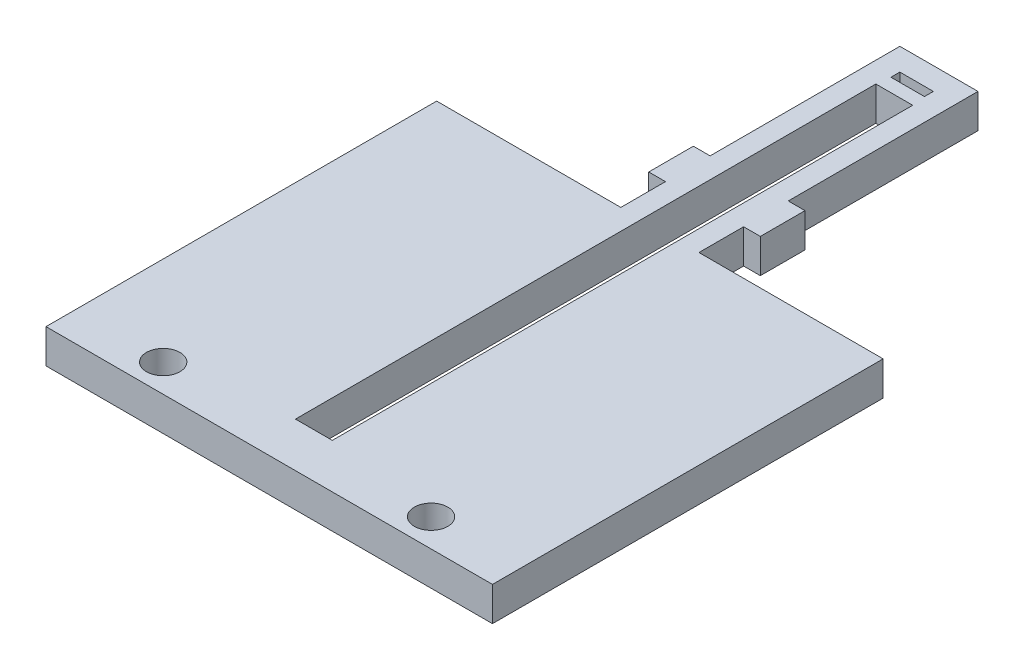
SolidWorks part; units mm, degrees
ref_plane "Front Plane" through (0, 0, 0) normal (0, 0, 1) x (1, 0, 0)
ref_plane "Top Plane" through (0, 0, 0) normal (0, 1, 0) x (1, 0, 0)
ref_plane "Right Plane" through (0, 0, 0) normal (1, 0, 0) x (0, 0, -1)
sketch "Sketch1" plane through (0, 0, 0) normal (0, 1, 0) x (1, 0, 0)
  line L1 (0, 0) -> (40, 0)
  line L2 (0, 0) -> (0, 60)
  line L3 (0, 60) -> (40, 60)
  line L4 (40, 0) -> (40, 60)
  dimension "D1" = 40
  dimension "D2" = 60
extrude "Boss-Extrude1" add sketch "Sketch1" along normal blind 3.05
sketch "Sketch4" plane through (0, 3.05, 0) normal (0, 1, 0) x (1, 0, 0)
  line L0 (20, 60) -> (20, 58)
  line L1 (0, 60) -> (40, 60) construction
  line L3 (21.5, 58) -> (18.5, 58)
  line L4 (18.5, 58) -> (18.5, 57.2)
  line L5 (18.5, 57.2) -> (21.5, 57.2)
  line L6 (21.5, 57.2) -> (21.5, 58)
  line L7 (20, 57.2) -> (20, 56)
  line L9 (21.65, 56) -> (18.35, 56)
  line L10 (18.35, 56) -> (18.35, 4)
  line L11 (18.35, 4) -> (21.65, 4)
  line L12 (21.65, 4) -> (21.65, 56)
  point P10 (20, 58)
  point P22 (20, 56)
  dimension "D1" = 2
  dimension "D2" = 0.8
  dimension "D3" = 1.2
  dimension "D4" = 3
  dimension "D5" = 52
  dimension "D6" = 3.3
extrude "Cut-Extrude1" cut sketch "Sketch4" against normal blind 10 contours L11 L12 L9 L10 | L5 L6 L3 L4
sketch "Sketch5" plane through (0, 3.05, 0) normal (0, 1, 0) x (1, 0, 0)
  line L0 (0, 60) -> (0, 20)
  line L1 (0, 0) -> (0, 60) construction
  line L2 (0, 60) -> (15, 60)
  line L3 (0, 60) -> (40, 60) construction
  line L5 (40, 60) -> (25, 60)
  line L6 (40, 60) -> (40, 20)
  line L7 (40, 0) -> (40, 60) construction
  line L9 (15, 60) -> (15, 20)
  line L10 (15, 20) -> (0, 20)
  line L11 (25, 60) -> (25, 20)
  line L12 (25, 20) -> (40, 20)
  circle A0 centre (7.5, 27.5) radius 7.5
  circle A1 centre (32.5, 27.5) radius 7.5
  line M14 (40, 0) -> (40, 60)
  line M15 (40, 60) -> (0, 60)
  line M16 (0, 60) -> (0, 0)
  dimension "D1" = 40
  dimension "D2" = 15
  dimension "D3" = 40
  dimension "D4" = 15
extrude "Cut-Extrude2" [suppressed] cut sketch "Sketch5" against normal blind 10 contours A0 L9 M15 M16 | A0 | A0 L0 L10 | A1 L6 L11 M15 | A1 | A1 L12 M14
sketch "Sketch6" plane through (0, 3.05, 0) normal (0, 1, 0) x (1, 0, 0)
  line L0 (0, 60) -> (0, 35)
  line L1 (0, 0) -> (0, 60) construction
  line L2 (0, 60) -> (16.5, 60)
  line L3 (0, 60) -> (40, 60) construction
  line L4 (40, 60) -> (40, 35)
  line L5 (40, 0) -> (40, 60) construction
  line L6 (40, 60) -> (23.5, 60)
  line L9 (0, 35) -> (16.5, 35)
  line L12 (23.5, 35) -> (40, 35)
  line L13 (16.5, 35) -> (16.5, 39)
  line L14 (16.5, 39) -> (15, 39)
  line L15 (15, 39) -> (15, 43)
  line L16 (15, 43) -> (16.5, 43)
  line L17 (16.5, 43) -> (16.5, 60)
  line L18 (23.5, 35) -> (23.5, 39)
  line L19 (23.5, 39) -> (25, 39)
  line L20 (25, 39) -> (25, 43)
  line L21 (25, 43) -> (23.5, 43)
  line L22 (23.5, 43) -> (23.5, 60)
  dimension "D1" = 25
  dimension "D2" = 16.5
  dimension "D3" = 25
  dimension "D4" = 16.5
  dimension "D5" = 4
  dimension "D6" = 4
  dimension "D7" = 1.5
  dimension "D8" = 16.5
  dimension "D9" = 1.5
  dimension "D10" = 4
  dimension "D11" = 4
  dimension "D12" = 16.5
extrude "Cut-Extrude3" cut sketch "Sketch6" against normal blind 10
sketch "Sketch7" plane through (0, 3.05, 0) normal (0, 1, 0) x (1, 0, 0)
  line L0 (0, 0) -> (40, 0) construction
  line L1 (0, 0) -> (8, 0)
  line L2 (8, 0) -> (8, 2.5)
  line L3 (8, 2.5) -> (32, 2.5)
  circle A0 centre (8, 2.5) radius 1.5
  circle A1 centre (32, 2.5) radius 1.5
  dimension "D3" = 3
  dimension "D5" = 3
  dimension "D1" = 8
  dimension "D2" = 2.5
  dimension "D4" = 24
extrude "Cut-Extrude4" cut sketch "Sketch7" against normal blind 10
